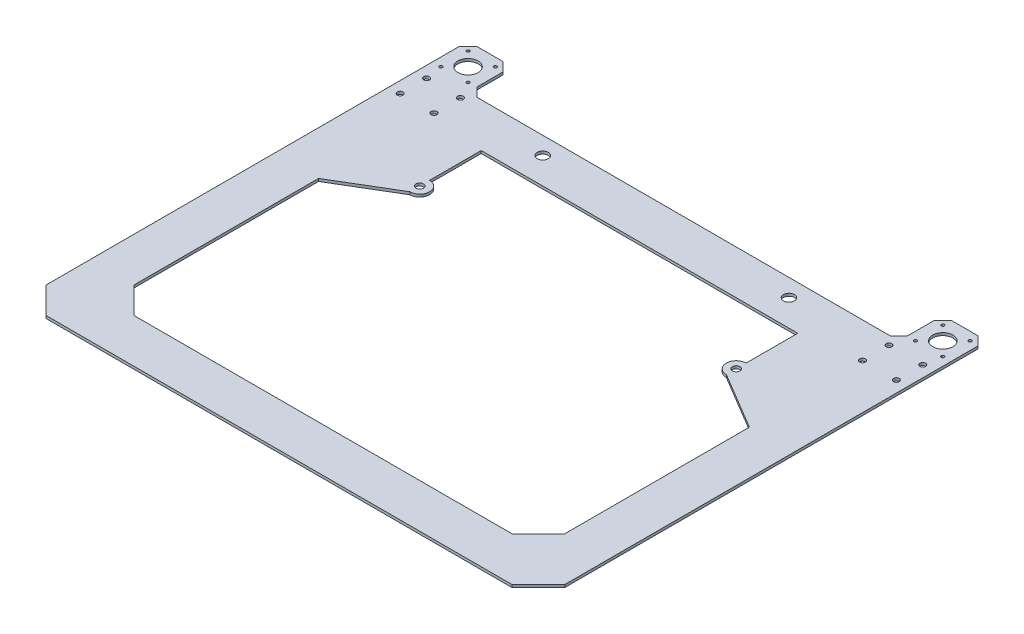
SolidWorks part; units mm, degrees
ref_plane "Front Plane" through (0, 0, 0) normal (0, 0, 1) x (1, 0, 0)
ref_plane "Top Plane" through (0, 0, 0) normal (0, 1, 0) x (1, 0, 0)
ref_plane "Right Plane" through (0, 0, 0) normal (1, 0, 0) x (0, 0, -1)
sketch "Sketch1" plane through (0, 0, 0) normal (0, 1, 0) x (1, 0, 0)
  line L0 (-249.3423, 210) -> (295, 210) construction
  line L1 (-245, 230) -> (295, 230)
  line L2 (-295, 230) -> (-295, -230)
  line L3 (-295, -230) -> (295, -230)
  line L4 (295, 230) -> (295, -230)
  line L5 (-295, 230) -> (295, -230) construction
  line L6 (-295, -230) -> (295, 230) construction
  line L7 (-180, 180) -> (180, 180)
  line L8 (-245, 60) -> (-245, -180)
  line L9 (-245, -180) -> (245, -180)
  line L10 (245, 60) -> (245, -180)
  line L11 (-210.8756, 154.929) -> (245, -180) construction
  line L12 (-245, -180) -> (210.8756, 154.929) construction
  line L13 (-295, 110) -> (295, 110) construction
  line L14 (-180, 121.25) -> (-180, 180)
  line L15 (-180.0041, 98.75) -> (-245, 60)
  line L16 (180, 121.25) -> (180, 180)
  line L17 (180, 98.75) -> (245, 60)
  line L18 (245, 230) -> (245, 154.929) construction
  line L19 (245, 154.929) -> (295, 154.929) construction
  line L20 (243.6957, 220) -> (243.6957, 190) construction
  line L21 (243.6957, 190) -> (282.1739, 190) construction
  line L22 (282.1739, 190) -> (282.1739, 220) construction
  line L23 (282.1739, 220) -> (243.6957, 220) construction
  line L24 (0, 180) -> (0, 157.8469) construction
  line L25 (-282.1739, 220) -> (-282.1739, 190) construction
  line L26 (-282.1739, 190) -> (-243.6957, 190) construction
  line L27 (-243.6957, 190) -> (-243.6957, 220) construction
  line L28 (-243.6957, 220) -> (-282.1739, 220) construction
  line L29 (-295, 230) -> (-295, 280)
  line L30 (-295, 280) -> (-245, 280)
  line L31 (-245, 280) -> (-245, 230)
  line L32 (-295, 280) -> (-245, 230) construction
  line L33 (-295, 230) -> (-245, 280) construction
  line L34 (-285.5, 270.5) -> (-285.5, 239.5) construction
  line L35 (-285.5, 239.5) -> (-254.5, 239.5) construction
  line L36 (-254.5, 239.5) -> (-254.5, 270.5) construction
  line L37 (-254.5, 270.5) -> (-285.5, 270.5) construction
  circle A0 centre (-140, 210) radius 6.25
  circle A1 centre (140, 210) radius 6.25
  circle A2 centre (-180, 110) radius 4.25
  circle A3 centre (180, 110) radius 4.25
  arc A4 (-180, 121.25) -> (-180.0041, 98.75) centre (-180, 110) cw
  arc A5 (180, 121.25) -> (180, 98.75) centre (180, 110) ccw
  circle A6 centre (243.6957, 220) radius 3.25
  circle A7 centre (282.1739, 220) radius 3.25
  circle A8 centre (282.1739, 190) radius 3.25
  circle A9 centre (243.6957, 190) radius 3.25
  circle A10 centre (-282.1739, 220) radius 3.25
  circle A11 centre (-243.6957, 220) radius 3.25
  circle A12 centre (-243.6957, 190) radius 3.25
  circle A13 centre (-282.1739, 190) radius 3.25
  circle A14 centre (-270, 255) radius 11.5
  circle A15 centre (-285.5, 239.5) radius 1.75
  circle A16 centre (-285.5, 270.5) radius 1.75
  circle A17 centre (-254.5, 270.5) radius 1.75
  circle A18 centre (-254.5, 239.5) radius 1.75
  point P0 (0, 0)
  point P6 (0, 0)
  dimension "D4" = 12.5
  dimension "D5" = 12.5
  dimension "D10" = 8.5
  dimension "D11" = 8.5
  dimension "D13" = 11.25
  dimension "D18" = 6.5
  dimension "D22" = 23
  dimension "D23" = 3.5
  dimension "D1" = 590
  dimension "D2" = 460
  dimension "D3" = 50
  dimension "D6" = 280
  dimension "D7" = 50
  dimension "D8" = 100
  dimension "D9" = 360
  dimension "D12" = 10
  dimension "D14" = 50
  dimension "D15" = 50
  dimension "D16" = 0
  dimension "D17" = 30
  dimension "D19" = 20
  dimension "D20" = 31
  dimension "D21" = 50
  dimension "D24" = 31
  dimension "D25" = 50
  dimension "D26" = 50
  dimension "D27" = 140
extrude "Boss-Extrude1" add sketch "Sketch1" along normal blind 3
sketch "Sketch2" plane through (0, 3, 0) normal (0, 1, 0) x (1, 0, 0)
  line L0 (245, 280) -> (295, 230) construction
  line L1 (295, 230) -> (245, 230)
  line L2 (295, 230) -> (295, 280)
  line L3 (295, 280) -> (245, 280)
  line L4 (245, 230) -> (245, 280)
  line L5 (295, 280) -> (245, 230) construction
  line L6 (254.5, 270.5) -> (254.5, 239.5) construction
  line L7 (254.5, 239.5) -> (285.5, 239.5) construction
  line L8 (285.5, 239.5) -> (285.5, 270.5) construction
  line L9 (285.5, 270.5) -> (254.5, 270.5) construction
  circle A0 centre (270, 255) radius 11.5
  circle A1 centre (254.5, 270.5) radius 1.75
  circle A2 centre (285.5, 270.5) radius 1.75
  circle A3 centre (254.5, 239.5) radius 1.75
  circle A4 centre (285.5, 239.5) radius 1.75
  dimension "D2" = 3.5
  dimension "D3" = 23
  dimension "D1" = 50
  dimension "D4" = 31
extrude "Boss-Extrude2" add sketch "Sketch2" against normal up to surface (3 mm away) up to face at (-81.6667, 0, -93.3333)
chamfer "Chamfer1" distance 10 angle 45 6 edges at (295, 1.5, -280) (245, 1.5, -280) (245, 1.5, -230) (-245, 1.5, -230) (-245, 1.5, -280) (-295, 1.5, -280)
chamfer "Chamfer2" distance 30 angle 45 4 edges at (295, 1.5, 230) (245, 1.5, 180) (-295, 1.5, 230) (-245, 1.5, 180)
